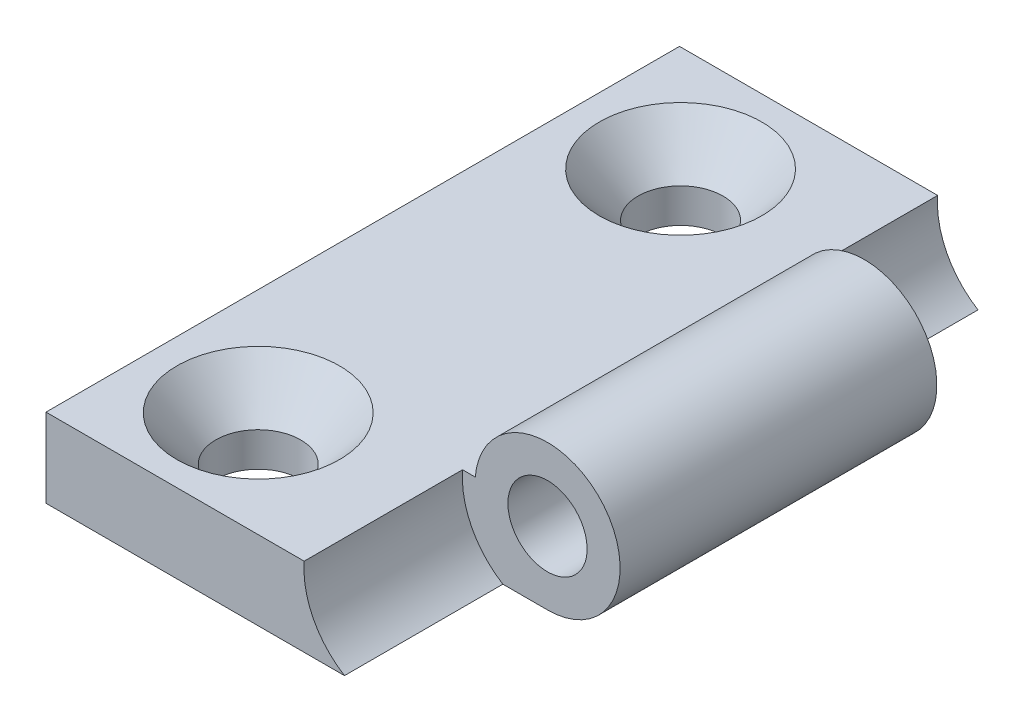
SolidWorks part; units mm, degrees
ref_plane "Front" through (0, 0, 0) normal (0, 0, 1) x (1, 0, 0)
ref_plane "Top" through (0, 0, 0) normal (0, 1, 0) x (1, 0, 0)
ref_plane "Right" through (0, 0, 0) normal (1, 0, 0) x (0, 0, -1)
sketch "Sketch1" plane through (0, 0, 0) normal (0, 0, 1) x (1, 0, 0)
  line L0 (-20.6375, 0) -> (0, 0)
  line L2 (-20.6375, 0) -> (-20.6375, 4.7498)
  line L3 (-20.6375, 4.7498) -> (-4.3487, 4.7498)
  circle A0 centre (0, 4.3656) radius 2.3813
  arc A1 (4.3487, 4.7498) -> (-4.3487, 4.7498) centre (0, 4.3656) ccw
  arc A2 (0, 0) -> (4.3487, 4.7498) centre (0, 4.3656) ccw
  dimension "D1" = 8.7312
  dimension "D3" = 4.7625
  dimension "D2" = 4.7498
  dimension "D4" = 20.6375
extrude "Extrude1" add sketch "Sketch1" along normal mid plane 38.1
sketch "Sketch2" plane through (0, 0, 19.05) normal (0, 0, 1) x (1, 0, 0)
  line L0 (-5.1107, 4.7498) -> (-4.3487, 4.7498)
  line L1 (0, 0) -> (-2.6848, 0)
  arc A0 (-4.3487, 4.7498) -> (0, 0) centre (0.4196, 4.7498) cw
  arc A2 (-5.1107, 4.7498) -> (-2.6848, 0) centre (0, 4.3656) ccw
  dimension "D1" = 0.762
extrude "Cut-Extrude1" cut sketch "Sketch2" against normal blind 9.525
mirror "Mirror1" about plane through (0, 0, 0) normal (0, 0, 1) of "Cut-Extrude1"
sketch "Sketch5" plane through (0, 0, 0) normal (0, 0, 1) x (1, 0, 0)
  circle A0 centre (0, 4.3656) radius 2.3813
  dimension "D1" = 4.7625
hole_wizard "CSK for #10 Flat Head Machine Screw1" positions "Sketch7" profile "Sketch6" countersink size "#10" standard "Ansi Inch" end condition through all
sketch "Sketch7" plane through (0, 4.7498, 0) normal (0, 1, 0) x (-1, 0, 0)
  line L0 (0, 20.2095) -> (0, -21.445) construction
  line L1 (-8.9184, 0) -> (9.9085, 0) construction
  point P0 (14.224, -12.7)
  point P1 (14.224, 12.7)
sketch "Sketch6" plane through (-14.224, 4.7498, -12.7) normal (1, 0, 0) x (0, 0, 1)
  line L0 (0, 0) -> (0, 4.7498)
  line L1 (0, 4.7498) -> (2.5527, 4.7498)
  line L2 (2.5527, 4.7498) -> (2.5527, 2.6882)
  line L3 (2.5527, 2.6882) -> (4.8895, 0)
  line L5 (4.8895, 0) -> (0, 0)
  line L6 (-2.5527, 2.6882) -> (-4.8895, 0) construction
  line L11 (0, -6.35) -> (0, 107.95) construction
  dimension "Thru Hole Dia." = 5.1054
  dimension "Thru Hole Depth" = 4.7498
  dimension "Near C'Sink Dia." = 9.779
  dimension "Near C'Sink Angle" = 82
